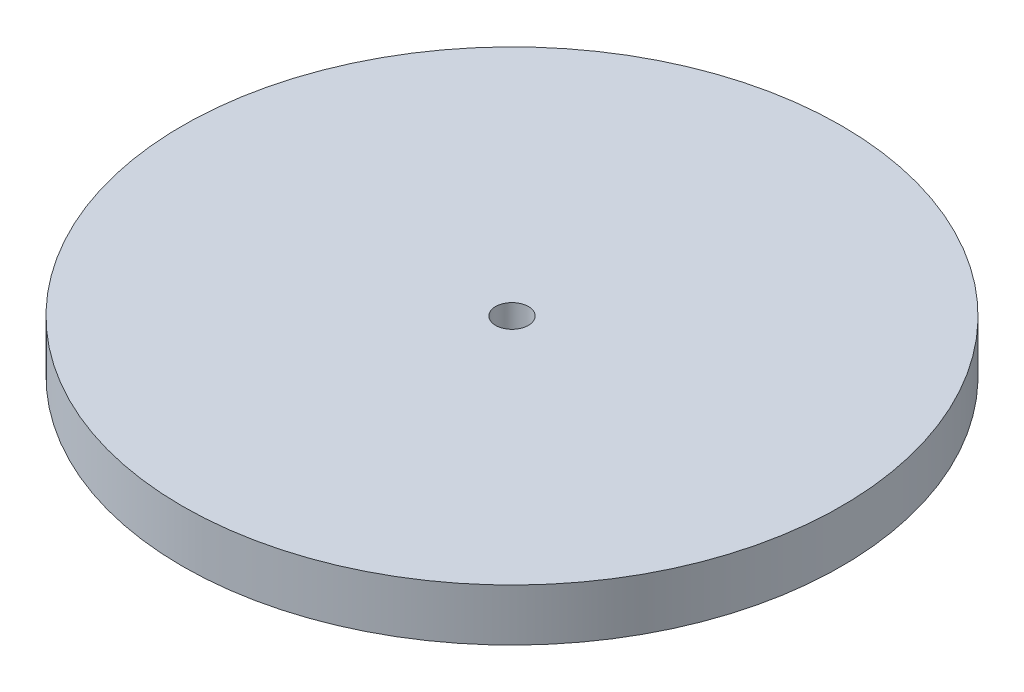
SolidWorks part; units mm, degrees
ref_plane "Front Plane" through (0, 0, 0) normal (0, 0, 1) x (1, 0, 0)
ref_plane "Top Plane" through (0, 0, 0) normal (0, 1, 0) x (1, 0, 0)
ref_plane "Right Plane" through (0, 0, 0) normal (1, 0, 0) x (0, 0, -1)
sketch "Sketch2" plane through (0, 0, 0) normal (0, 1, 0) x (1, 0, 0)
  circle A0 centre (0, 0) radius 120.65
  circle A1 centre (0, 0) radius 6
  dimension "D1" = 241.3
  dimension "D2" = 12
extrude "Boss-Extrude1" add sketch "Sketch2" along normal mid plane 19.05
